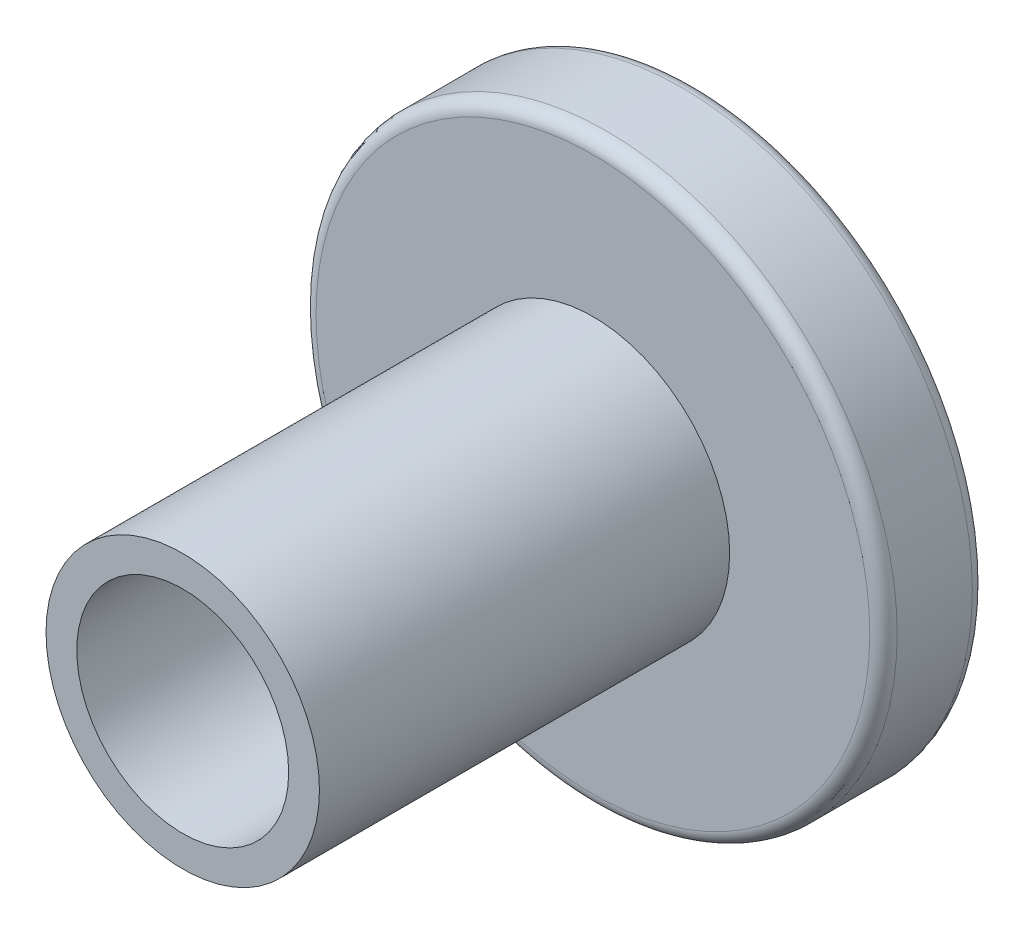
SolidWorks part; units mm, degrees
material "AISI 304"
ref_plane "前视基准面" through (0, 0, 0) normal (0, 0, 1) x (1, 0, 0)
ref_plane "上视基准面" through (0, 0, 0) normal (0, 1, 0) x (1, 0, 0)
ref_plane "右视基准面" through (0, 0, 0) normal (1, 0, 0) x (0, 0, -1)
other "Configuration Table"
sketch "草图1" plane through (0, 0, 0) normal (0, 0, 1) x (1, 0, 0)
  circle A0 centre (0, 0) radius 4.25
  dimension "D1" = 8.5
extrude "凸台-拉伸1" add sketch "草图1" along normal blind 1.5
sketch "草图2" plane through (0, 0, 1.5) normal (0, 0, 1) x (1, 0, 0)
  circle A0 centre (0, 0) radius 2
  circle A1 centre (0, 0) radius 1.55
  dimension "D1" = 4
  dimension "D2" = 3.1
extrude "凸台-拉伸2" add sketch "草图2" along normal blind 6
fillet "圆角1" radius 0.2 2 edges at (4.25, 0, 0) (4.25, 0, 1.5)
sketch "草图3" plane through (0, 0, 0) normal (0, 0, -1) x (-1, 0, 0)
  line L0 (0, 0) -> (1.4434, 0) construction
  line L1 (1.4434, 0) -> (0.7217, 1.25)
  line L2 (0.7217, 1.25) -> (-0.7217, 1.25)
  line L3 (-0.7217, 1.25) -> (-1.4434, 0)
  line L4 (-1.4434, 0) -> (-0.7217, -1.25)
  line L5 (-0.7217, -1.25) -> (0.7217, -1.25)
  line L6 (0.7217, -1.25) -> (1.4434, 0)
  circle A0 centre (0, 0) radius 1.25 construction
  dimension "D1" = 2.5
extrude "切除-拉伸1" cut sketch "草图3" against normal blind 1.5
